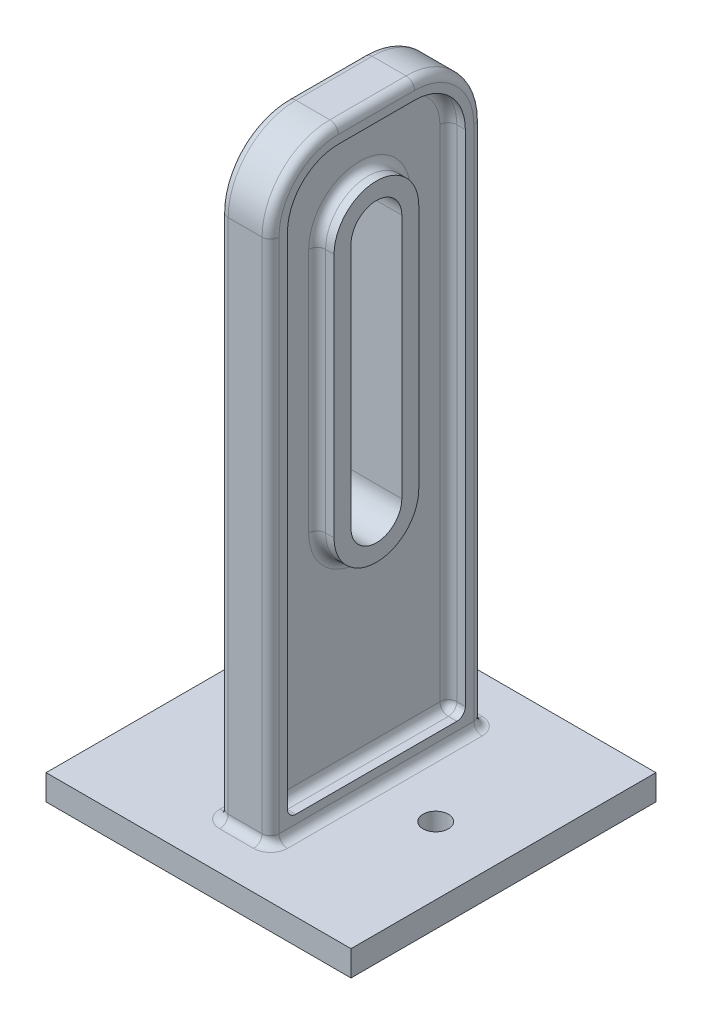
SolidWorks part; units mm, degrees
ref_plane "Front Plane" through (0, 0, 0) normal (0, 0, 1) x (1, 0, 0)
ref_plane "Top Plane" through (0, 0, 0) normal (0, 1, 0) x (1, 0, 0)
ref_plane "Right Plane" through (0, 0, 0) normal (1, 0, 0) x (0, 0, -1)
sketch "Sketch1" plane through (0, 0, 0) normal (0, 1, 0) x (1, 0, 0)
  line L1 (-18, 18) -> (18, 18)
  line L2 (-18, 18) -> (-18, -18)
  line L3 (-18, -18) -> (18, -18)
  line L4 (18, 18) -> (18, -18)
  line L5 (-18, 18) -> (18, -18) construction
  line L6 (-18, -18) -> (18, 18) construction
  point P0 (0, 0)
  dimension "D1" = 36
  dimension "D2" = 36
extrude "Boss-Extrude1" add sketch "Sketch1" along normal blind 3
sketch "Sketch2" plane through (0, 3, 0) normal (0, 1, 0) x (1, 0, 0)
  line L0 (0, 0) -> (0, 18.6621) construction
  line L1 (0, 0) -> (-19.8879, 0) construction
  circle A0 centre (-10, 0) radius 1.5
  circle A1 centre (10, 0) radius 1.5
  dimension "D2" = 3
  dimension "D1" = 10
extrude "Cut-Extrude1" cut sketch "Sketch2" against normal blind 3
sketch "Sketch3" plane through (0, 3, 0) normal (0, 1, 0) x (1, 0, 0)
  line L1 (-3, 12.5) -> (3, 12.5)
  line L2 (-3, 12.5) -> (-3, -12.5)
  line L3 (-3, -12.5) -> (3, -12.5)
  line L4 (3, 12.5) -> (3, -12.5)
  line L5 (-3, 12.5) -> (3, -12.5) construction
  line L6 (-3, -12.5) -> (3, 12.5) construction
  point P0 (0, 0)
  dimension "D1" = 6
  dimension "D2" = 25
extrude "Boss-Extrude2" add sketch "Sketch3" along normal blind 70
sketch "Sketch4" plane through (3, 0, 0) normal (1, 0, 0) x (0, 0, -1)
  line L0 (0, 73) -> (0, -6.2124) construction
  line L1 (-12.5, 73) -> (12.5, 73) construction
  line L2 (-3, 60) -> (3, 60) construction
  line L3 (-3, 60) -> (-3, 31)
  line L4 (3, 60) -> (3, 31)
  line L5 (-3, 45.5) -> (7.0382, 45.5) construction
  arc A0 (-3, 60) -> (3, 60) centre (0, 60) cw
  arc A1 (-3, 31) -> (3, 31) centre (0, 31) ccw
  point P8 (0, 63)
  point P13 (3, 45.5)
  dimension "D1" = 3
  dimension "D2" = 10
  dimension "D3" = 14.5
extrude "Cut-Extrude2" cut sketch "Sketch4" against normal blind 70
fillet "Fillet1" radius 8 2 edges at (0, 73, 12.5) (0, 73, -12.5)
sketch "Sketch5" plane through (3, 0, 0) normal (1, 0, 0) x (0, 0, -1)
  line L12 (4.5, 71) -> (-4.5, 71)
  line L13 (-10.5, 65) -> (-10.5, 5)
  line L14 (-10.5, 5) -> (10.5, 5)
  line L15 (10.5, 5) -> (10.5, 65)
  line L16 (4.5, 71) -> (-4.5, 71)
  line L17 (-10.5, 65) -> (-10.5, 5)
  line L18 (-10.5, 5) -> (10.5, 5)
  line L19 (10.5, 5) -> (10.5, 65)
  arc A6 (-4.5, 71) -> (-10.5, 65) centre (-4.5, 65) ccw
  arc A7 (10.5, 65) -> (4.5, 71) centre (4.5, 65) ccw
  arc A8 (-4.5, 71) -> (-10.5, 65) centre (-4.5, 65) ccw
  arc A9 (10.5, 65) -> (4.5, 71) centre (4.5, 65) ccw
  dimension "D1" = 2
extrude "Cut-Extrude3" cut sketch "Sketch5" against normal blind 2
sketch "Sketch6" plane through (1, 0, 0) normal (1, 0, 0) x (0, 0, -1)
  line L12 (-5, 60) -> (-5, 31)
  line L13 (5, 31) -> (5, 60)
  line L14 (-5, 60) -> (-5, 31)
  line L15 (5, 31) -> (5, 60)
  line L24 (3, 31) -> (3, 60)
  line L25 (-3, 60) -> (-3, 31)
  line L26 (3, 31) -> (3, 60)
  line L27 (-3, 60) -> (-3, 31)
  arc A10 (-5, 31) -> (5, 31) centre (0, 31) ccw
  arc A11 (5, 60) -> (-5, 60) centre (0, 60) ccw
  arc A12 (-5, 31) -> (5, 31) centre (0, 31) ccw
  arc A13 (5, 60) -> (-5, 60) centre (0, 60) ccw
  arc A21 (-3, 31) -> (3, 31) centre (0, 31) ccw
  arc A22 (3, 60) -> (-3, 60) centre (0, 60) ccw
  arc A23 (-3, 31) -> (3, 31) centre (0, 31) ccw
  arc A24 (3, 60) -> (-3, 60) centre (0, 60) ccw
  dimension "D1" = 2
  dimension "D2" = 0
extrude "Boss-Extrude3" add sketch "Sketch6" along normal blind 2
mirror "Mirror1" about plane through (0, 0, 0) normal (1, 0, 0) of "Boss-Extrude3", "Cut-Extrude3"
fillet "Fillet2" radius 1 38 edges at (-1, 35, 10.5) (-1, 69.2426, 8.7426) (-1, 71, 0) (-1, 69.2426, -8.7426) (-1, 45.5, 5) (-1, 65, 0) (-1, 45.5, -5) (-3, 34, 12.5) (-3, 70.6569, 10.1569) (-3, 73, 0) (-3, 70.6569, -10.1569) (1, 26, 0) (1, 45.5, 5) (1, 5, 0) (-1, 5, 0) (-3, 3, 0) (-1, 35, -10.5) (-1, 26, 0) (-3, 34, -12.5) (0, 3, -12.5) (1, 45.5, -5) (1, 65, 0) (3, 34, -12.5) (3, 70.6569, -10.1569) (3, 73, 0) (3, 70.6569, 10.1569) (3, 34, 12.5) (0, 3, 12.5) (3, 3, 0) (1, 69.2426, 8.7426) (1, 71, 0) (1, 69.2426, -8.7426) (1, 35, 10.5) (1, 35, -10.5) (-2, 5, 10.5) (-2, 5, -10.5) (2, 5, -10.5) (2, 5, 10.5)
